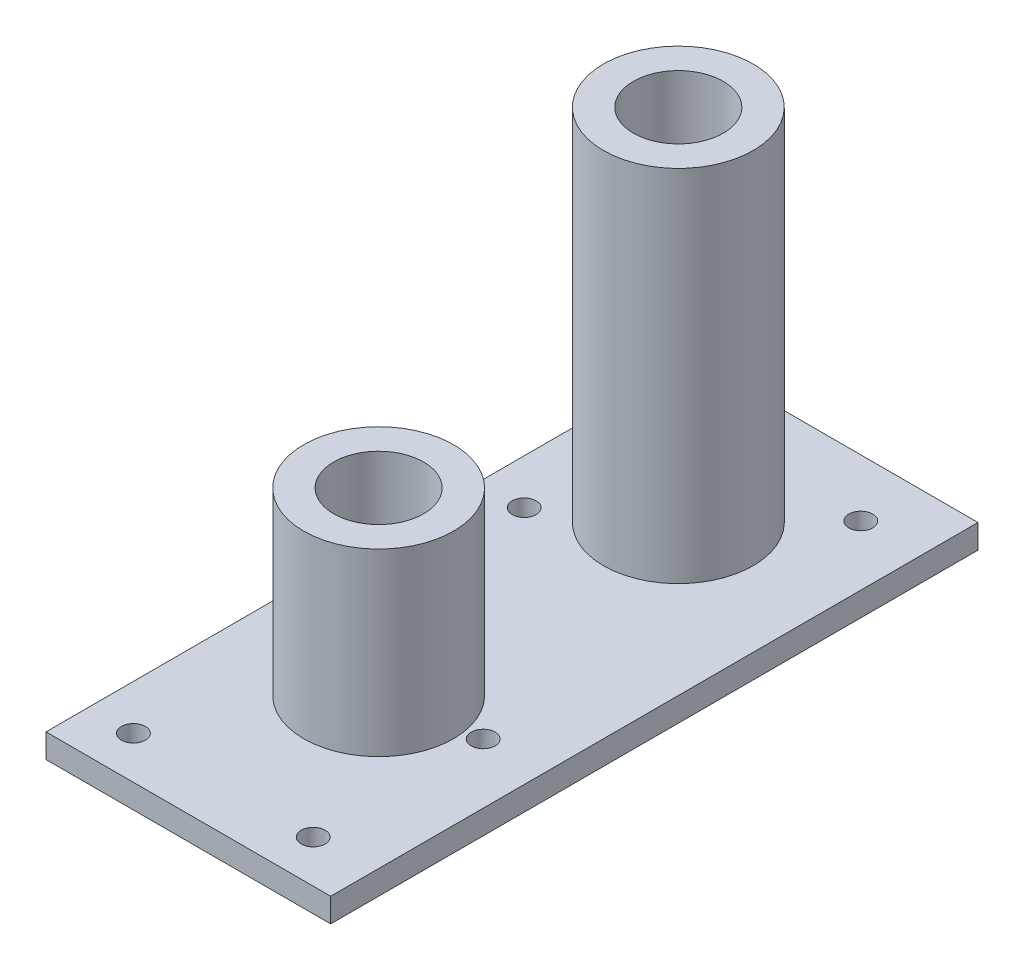
SolidWorks part; units mm, degrees
ref_plane "Płaszczyzna przednia" through (0, 0, 0) normal (0, 0, 1) x (1, 0, 0)
ref_plane "Płaszczyzna górna" through (0, 0, 0) normal (0, 1, 0) x (1, 0, 0)
ref_plane "Płaszczyzna prawa" through (0, 0, 0) normal (1, 0, 0) x (0, 0, -1)
sketch "Sketch1" plane through (0, 0, 0) normal (0, 1, 0) x (1, 0, 0)
  line L1 (-19.1477, 6.875) -> (-9.1477, 6.875)
  line L2 (-19.1477, 6.875) -> (-19.1477, -3.125)
  line L3 (-19.1477, -3.125) -> (-9.1477, -3.125)
  line L4 (-9.1477, 6.875) -> (-9.1477, -3.125)
  line L5 (-19.1477, 6.875) -> (-9.1477, -3.125) construction
  line L6 (-19.1477, -3.125) -> (-9.1477, 6.875) construction
  line L7 (-19.1477, -43.125) -> (-9.1477, -43.125)
  line L8 (-19.1477, -43.125) -> (-19.1477, -53.125)
  line L9 (-19.1477, -53.125) -> (-9.1477, -53.125)
  line L10 (-9.1477, -43.125) -> (-9.1477, -53.125)
  line L11 (-19.1477, -43.125) -> (-9.1477, -53.125) construction
  line L12 (-19.1477, -53.125) -> (-9.1477, -43.125) construction
  line L13 (-36.6477, 26.875) -> (10.8523, 26.875)
  line L14 (-36.6477, 26.875) -> (-36.6477, -81.125)
  line L15 (-36.6477, -81.125) -> (10.8523, -81.125)
  line L16 (10.8523, 26.875) -> (10.8523, -81.125)
  circle A0 centre (0.8523, 17.315) radius 2
  circle A1 centre (-29.1477, -8.845) radius 2
  circle A2 centre (0.8523, -45.685) radius 2
  circle A3 centre (0.8523, -74.045) radius 2
  circle A4 centre (-29.1477, -74.045) radius 2
  point P0 (-14.6023, 1.875)
  point P5 (-2.5568, 5.0568)
  dimension "D3" = 4
  dimension "D4" = 4
  dimension "D5" = 4
  dimension "D6" = 4
  dimension "D7" = 4
  dimension "D1" = 10
  dimension "D2" = 40
  dimension "D8" = 10
  dimension "D9" = 10.44
  dimension "D10" = 15.72
  dimension "D11" = 10
  dimension "D12" = 30.92
  dimension "D13" = 10
  dimension "D14" = 10
  dimension "D15" = 20.92
  dimension "D16" = 2.56
  dimension "D17" = 10
  dimension "D18" = 20
  dimension "D19" = 17.5
  dimension "D20" = 20
  dimension "D21" = 28
extrude "Boss-Extrude1" add sketch "Sketch1" against normal blind 4
sketch "Sketch2" plane through (0, 0, 0) normal (0, 1, 0) x (1, 0, 0)
  line L0 (-19.1477, -3.125) -> (-9.1477, 6.875) construction
  line L1 (-19.1477, -53.125) -> (-9.1477, -43.125) construction
  circle A2 centre (-14.1477, -48.125) radius 12.5
  circle A3 centre (-14.1477, -48.125) radius 7.5
  point P5 (-14.1477, 1.875)
  dimension "D3" = 2
extrude "Boss-Extrude2" add sketch "Sketch2" along normal blind 30 contours A2 | A3
sketch "Sketch4" plane through (0, 0, 0) normal (0, 1, 0) x (1, 0, 0)
  line L0 (-19.1477, 6.875) -> (-9.1477, -3.125) construction
  circle A0 centre (-14.1477, 1.875) radius 12.5
  circle A1 centre (-14.1477, 1.875) radius 7.5
  point P7 (-14.1477, 1.875)
  dimension "D1" = 15
  dimension "D2" = 25
extrude "Boss-Extrude3" add sketch "Sketch4" along normal blind 60
